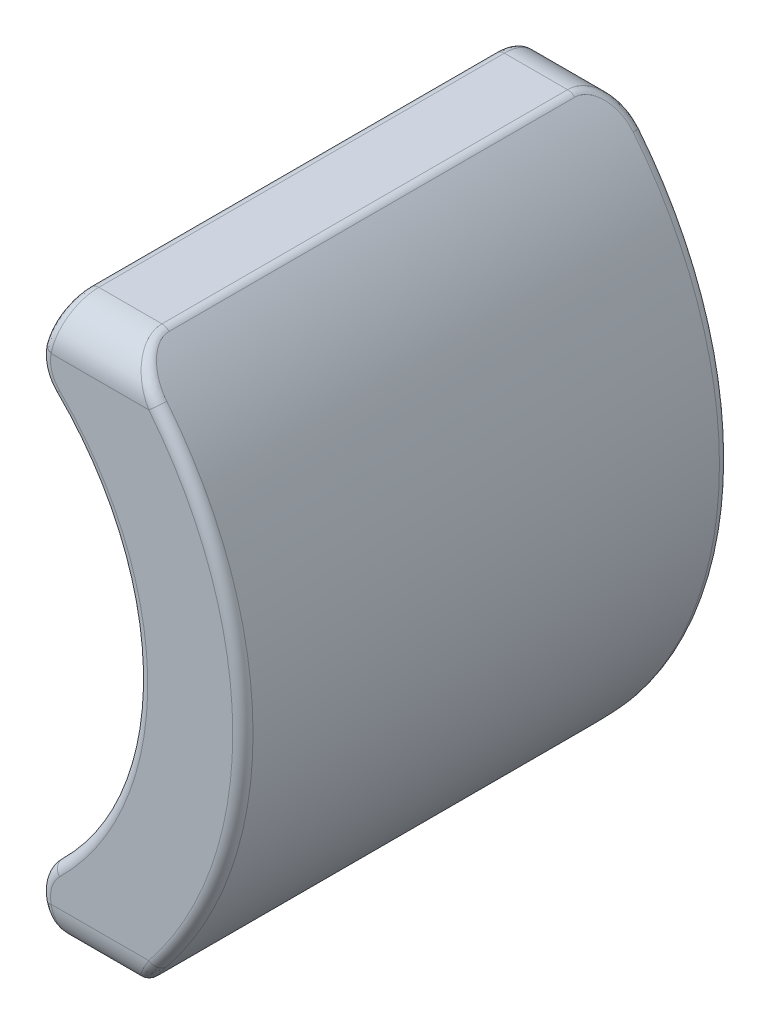
SolidWorks part; units mm, degrees
ref_plane "Front Plane" through (0, 0, 0) normal (0, 0, 1) x (1, 0, 0)
ref_plane "Top Plane" through (0, 0, 0) normal (0, 1, 0) x (1, 0, 0)
ref_plane "Right Plane" through (0, 0, 0) normal (1, 0, 0) x (0, 0, -1)
sketch "Sketch1" plane through (0, 0, 0) normal (0, 0, 1) x (1, 0, 0)
  line L0 (0, 0) -> (9.63, 0) construction
  line L1 (6.7381, -6.88) -> (4.8781, -6.88)
  line L2 (4.8781, -6.88) -> (4.5318, -5.38)
  line L3 (6.7381, 6.88) -> (4.8781, 6.88)
  line L4 (4.8781, 6.88) -> (4.5318, 5.38)
  arc A0 (6.7381, 6.88) -> (6.7381, -6.88) centre (0, 0) cw
  arc A1 (4.5318, 5.38) -> (4.5318, -5.38) centre (0, 0) cw
  dimension "D1" = 9.63
  dimension "D2" = 6.88
  dimension "D4" = 1.86
  dimension "D5" = 103
  dimension "D6" = 1.5
extrude "Boss-Extrude1" add sketch "Sketch1" along normal mid plane 12
fillet "Fillet1" radius 1 2 edges at (4.5318, -5.38, 0) (4.5318, 5.38, 0)
fillet "Fillet2" radius 1 4 edges at (5.8081, -6.88, -6) (5.8081, 6.88, -6) (5.8081, -6.88, 6) (5.8081, 6.88, 6)
fillet "Fillet3" radius 0.25 24 edges at (4.8161, -6.6112, -5.6822) (4.8781, -6.88, 0) (4.8161, -6.6112, 5.6822) (4.6879, -5.4113, 6) (7.0343, 0, 6) (4.6879, 5.4113, 6) (4.8161, 6.6112, 5.6822) (4.8781, 6.88, 0) (4.8161, 6.6112, -5.6822) (6.8685, -6.7498, -5.4934) (6.7381, -6.88, 0) (6.9882, -6.6258, 5.6661) (9.63, 0, 6) (6.8685, 6.7498, 5.4934) (6.7381, 6.88, 0) (6.9882, 6.6258, -5.6661) (4.6879, 5.4113, -6) (7.0343, 0, -6) (4.6879, -5.4113, -6) (9.63, 0, -6)
